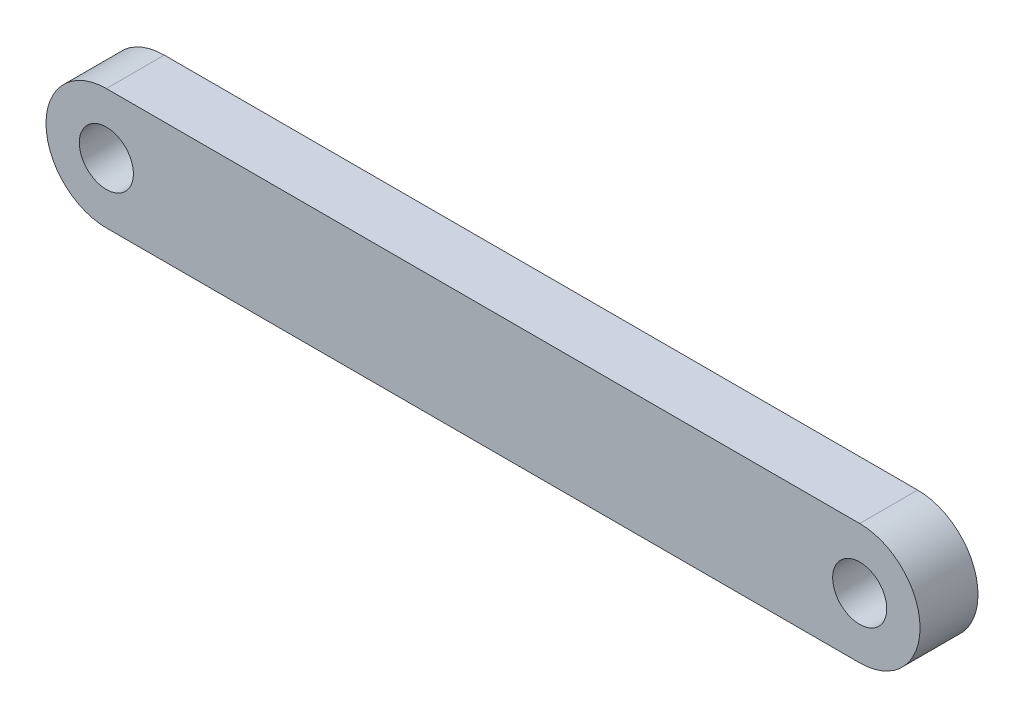
SolidWorks part; units mm, degrees
ref_plane "Front" through (0, 0, 0) normal (0, 0, 1) x (1, 0, 0)
ref_plane "Top" through (0, 0, 0) normal (0, 1, 0) x (1, 0, 0)
ref_plane "Right" through (0, 0, 0) normal (1, 0, 0) x (0, 0, -1)
sketch "Sketch1" plane through (0, 0, 0) normal (0, 0, 1) x (1, 0, 0)
  line L0 (0, 0) -> (39.624, 0) construction
  line L1 (0, 3.175) -> (39.624, 3.175)
  line L2 (0, -3.175) -> (39.624, -3.175)
  arc A0 (0, 3.175) -> (0, -3.175) centre (0, 0) ccw
  arc A1 (39.624, -3.175) -> (39.624, 3.175) centre (39.624, 0) ccw
  circle A2 centre (0, 0) radius 1.4224
  circle A3 centre (39.624, 0) radius 1.4224
  point P3 (19.812, 0)
  dimension "D2" = 2.8448
  dimension "D1" = 39.624
  dimension "D3" = 6.35
extrude "Boss-Extrude1" add sketch "Sketch1" along normal blind 3.048
